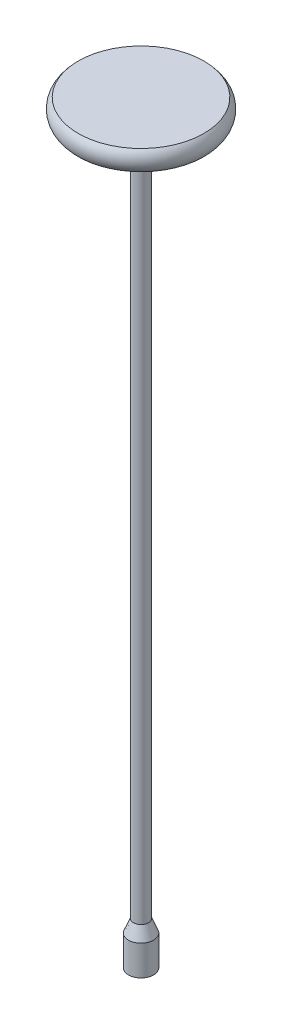
SolidWorks part; units mm, degrees
ref_plane "Front Plane" through (0, 0, 0) normal (0, 0, 1) x (1, 0, 0)
ref_plane "Top Plane" through (0, 0, 0) normal (0, 1, 0) x (1, 0, 0)
ref_plane "Right Plane" through (0, 0, 0) normal (1, 0, 0) x (0, 0, -1)
sketch "Sketch1" plane through (0, 0, 0) normal (0, 0, 1) x (1, 0, 0)
  line L0 (0, 0) -> (0, 318.0114) construction
  line L1 (0, 335.2327) -> (-25, 335.2327)
  line L3 (-25, 327.2327) -> (-5, 327.2327)
  line L5 (-3, 52.2327) -> (-5, 47.2327)
  line L6 (-5, 47.2327) -> (-5, 35.2327)
  line L7 (-5, 35.2327) -> (-4, 35.2327)
  line L8 (0, 46.2327) -> (0, 335.2327)
  line L9 (-5, 327.2327) -> (-5, 317.2327)
  line L11 (-3, 317.5207) -> (-3, 52.2327)
  line L12 (-5, 35.2327) -> (-4, 35.2327)
  line L13 (-4, 35.2327) -> (-4, 46.2327)
  line L14 (-4, 46.2327) -> (0, 46.2327)
  arc A1 (-25, 327.2327) -> (-25, 335.2327) centre (-21, 331.2327) cw
  spline S0 degree 2 poles (-5, 317.2327) (-3.9941, 317.3379) (-3, 317.5207) knots 0 0 0 1 1 1
  point P11 (-4, 47.2327)
  dimension "D9" = 5
  dimension "D1" = 300
  dimension "D2" = 8
  dimension "D3" = 3
  dimension "D4" = 5
  dimension "D5" = 12
  dimension "D6" = 5
  dimension "D7" = 10
  dimension "D8" = 25
  dimension "D10" = 1
  dimension "D11" = 11
revolve "Revolve2" add sketch "Sketch1" angle 360 about L0
